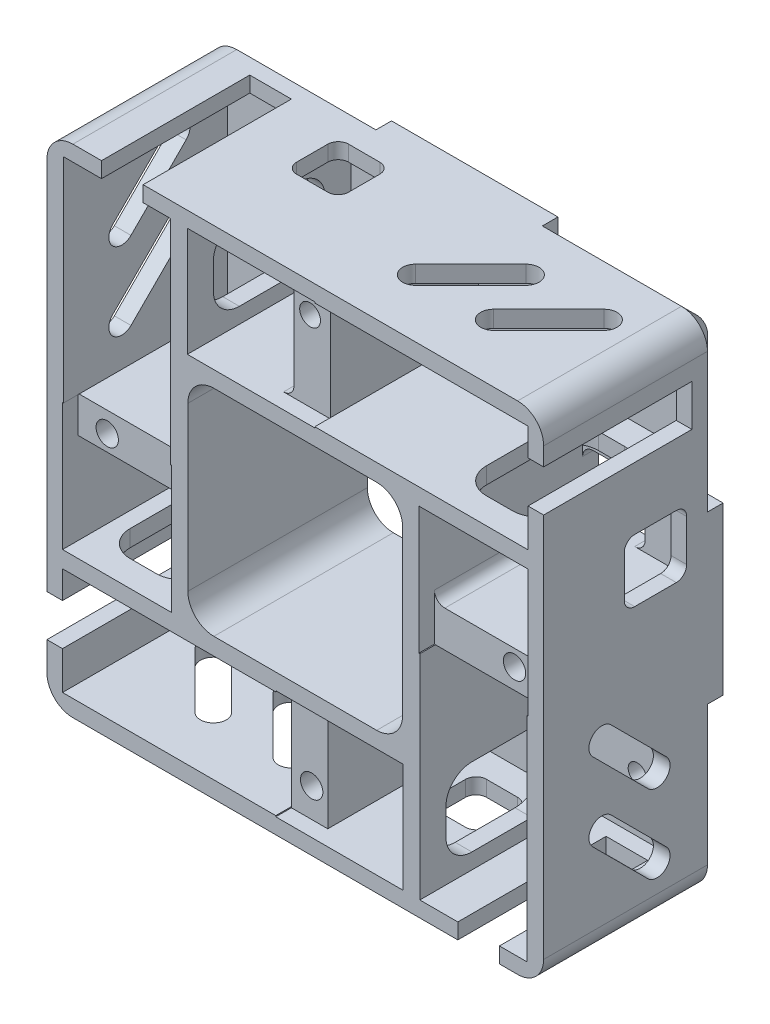
SolidWorks part; units mm, degrees
ref_plane "正面" through (0, 0, 0) normal (0, 0, 1) x (1, 0, 0)
ref_plane "平面" through (0, 0, 0) normal (0, 1, 0) x (1, 0, 0)
ref_plane "右側面" through (0, 0, 0) normal (1, 0, 0) x (0, 0, -1)
sketch "ｽｹｯﾁ1" plane through (0, 0, 0) normal (0, 0, 1) x (1, 0, 0)
  line L7 (47.75, -47.75) -> (-47.75, -47.75)
  line L8 (47.75, -47.75) -> (47.75, 47.75)
  line L9 (47.75, 47.75) -> (-47.75, 47.75)
  line L10 (-47.75, -47.75) -> (-47.75, 47.75)
  line L11 (47.75, -47.75) -> (-47.75, 47.75) construction
  line L12 (47.75, 47.75) -> (-47.75, -47.75) construction
  circle A0 centre (34.25, 34.25) radius 1.75
  circle A1 centre (-34.25, 34.25) radius 1.75
  circle A2 centre (-34.25, -34.25) radius 1.75
  circle A3 centre (34.25, -34.25) radius 1.75
  point P0 (0, 0)
  point P10 (0, 0)
  dimension "D1" = 95.5
  dimension "D2" = 13.5
  dimension "D3" = 13.5
  dimension "D4" = 13.5
  dimension "D5" = 13.5
  dimension "D6" = 13.5
  dimension "D7" = 13.5
  dimension "D8" = 13.5
  dimension "D9" = 13.5
  dimension "D10" = 3.5
extrude "ﾎﾞｽ - 押し出し1" add sketch "ｽｹｯﾁ1" along normal blind 3
sketch "ｽｹｯﾁ3" plane through (0, 0, 3) normal (0, 0, 1) x (1, 0, 0)
  line L29 (2.25, -23.75) -> (20.75, -23.75)
  line L30 (-47.75, 47.75) -> (47.75, 47.75)
  line L32 (-20.75, -2) -> (-20.75, -20.75)
  line L33 (-47.75, 47.75) -> (-47.75, -47.75)
  line L34 (-47.75, -47.75) -> (47.75, -47.75)
  line L35 (47.75, 47.75) -> (47.75, -47.75)
  line L36 (-44.75, 44.75) -> (-23.75, 44.75)
  line L37 (-44.75, 44.75) -> (-44.75, 3.75)
  line L38 (-44.75, 3.75) -> (-23.75, 3.75)
  line L39 (-23.75, 44.75) -> (-23.75, 3.75)
  line L40 (44.75, 44.75) -> (3.75, 44.75)
  line L42 (44.75, 23.75) -> (3.75, 23.75)
  line L43 (3.75, 44.75) -> (3.75, 23.75)
  line L44 (44.75, -44.75) -> (23.75, -44.75)
  line L45 (44.75, -44.75) -> (44.75, -3.75)
  line L46 (44.75, -3.75) -> (23.75, -3.75)
  line L47 (23.75, -44.75) -> (23.75, -3.75)
  line L48 (44.75, 44.75) -> (44.75, 23.75)
  line L49 (-44.75, -44.75) -> (-3.75, -44.75)
  line L50 (-44.75, -44.75) -> (-44.75, -23.75)
  line L51 (-44.75, -23.75) -> (-3.75, -23.75)
  line L52 (-3.75, -44.75) -> (-3.75, -23.75)
  line L54 (-20.75, 44.75) -> (-2.25, 44.75)
  line L55 (-20.75, 44.75) -> (-20.75, 23.75)
  line L57 (-2.25, 44.75) -> (-2.25, 23.75)
  line L58 (-44.75, -2.25) -> (-23.75, -2.25)
  line L59 (-44.75, -2.25) -> (-44.75, -20.75)
  line L60 (-44.75, -20.75) -> (20.75, -20.75)
  line L61 (20.75, 2) -> (20.75, -20.75)
  line L62 (-2, 20.75) -> (20.75, 20.75)
  line L64 (23.75, 2.25) -> (44.75, 2.25)
  line L65 (44.75, 20.75) -> (44.75, 2.25)
  line L66 (2.25, -44.75) -> (20.75, -44.75)
  line L67 (2.25, -44.75) -> (2.25, -20.75)
  line L69 (20.75, -44.75) -> (20.75, -23.75)
  line L70 (-20.75, -20.75) -> (-23.75, -20.75)
  line L71 (-23.75, -2.25) -> (-23.75, -20.75)
  line L72 (-2, 20.75) -> (-20.75, 20.75)
  line L74 (-2.25, 23.75) -> (-20.75, 23.75)
  line L75 (-20.75, 20.75) -> (-20.75, 23.75)
  line L77 (20.75, 2) -> (20.75, 20.75)
  line L78 (20.75, 20.75) -> (23.75, 20.75)
  line L79 (23.75, 2.25) -> (23.75, 20.75)
  line L80 (20.75, -20.75) -> (20.75, 2)
  line L81 (23.75, 20.75) -> (44.75, 20.75)
  line L82 (-20.75, 20.75) -> (-20.75, -2)
  dimension "D2" = 3
  dimension "D11" = 6
  dimension "D1" = 21
  dimension "D3" = 3
  dimension "D4" = 3
  dimension "D5" = 3
  dimension "D6" = 41
  dimension "D7" = 3
  dimension "D8" = 3
  dimension "D9" = 3
  dimension "D10" = 3
extrude "ﾎﾞｽ - 押し出し2" add sketch "ｽｹｯﾁ3" along normal blind 31.5
fillet "ﾌｨﾚｯﾄ1" radius 5 4 edges at (-47.75, -47.75, 17.25) (47.75, -47.75, 17.25) (47.75, 47.75, 17.25) (-47.75, 47.75, 17.25)
chamfer "面取り1" distance 3 angle 45 8 edges at (47.75, 0, 0) (46.2855, 46.2855, 0) (46.2855, -46.2855, 0) (0, 47.75, 0) (0, -47.75, 0) (-46.2855, 46.2855, 0) (-46.2855, -46.2855, 0) (-47.75, 0, 0)
sketch "ｽｹｯﾁ17" plane through (0, 0, 0) normal (0, 0, -1) x (-1, 0, 0)
  line L0 (-42.75, 47.75) -> (42.75, 47.75) construction
  line L1 (-16, 47.75) -> (16, 47.75)
  line L2 (-16, 47.75) -> (-16, 44.75)
  line L3 (-16, 44.75) -> (16, 44.75)
  line L4 (16, 47.75) -> (16, 44.75)
  line L5 (47.75, 42.75) -> (47.75, -42.75) construction
  line L6 (47.75, 16) -> (44.75, 16)
  line L7 (47.75, 16) -> (47.75, -16)
  line L8 (47.75, -16) -> (44.75, -16)
  line L9 (44.75, 16) -> (44.75, -16)
  line L10 (42.75, -47.75) -> (-42.75, -47.75) construction
  line L11 (16, -47.75) -> (-16, -47.75)
  line L12 (16, -47.75) -> (16, -44.75)
  line L13 (16, -44.75) -> (-16, -44.75)
  line L14 (-16, -47.75) -> (-16, -44.75)
  line L15 (-47.75, -42.75) -> (-47.75, 42.75) construction
  line L16 (-47.75, 16) -> (-44.75, 16)
  line L17 (-47.75, 16) -> (-47.75, -16)
  line L18 (-47.75, -16) -> (-44.75, -16)
  line L19 (-44.75, 16) -> (-44.75, -16)
  line L20 (42.75, 44.75) -> (-42.75, 44.75) construction
  line L21 (44.75, -42.75) -> (44.75, 42.75) construction
  line L22 (-42.75, -44.75) -> (42.75, -44.75) construction
  line L23 (-44.75, 42.75) -> (-44.75, -42.75) construction
  point P24 (-44.75, 0)
  point P26 (44.75, 0)
  point P27 (0, -44.75)
  point P28 (0, 44.75)
  dimension "D1" = 32
extrude "ﾎﾞｽ - 押し出し6" add sketch "ｽｹｯﾁ17" against normal blind 3
sketch "ｽｹｯﾁ19" plane through (0, 0, 0) normal (0, 0, -1) x (-1, 0, 0)
  line L0 (-47.75, 16) -> (-47.75, -16) construction
  line L1 (16, 47.75) -> (-16, 47.75) construction
  line L2 (47.75, -16) -> (47.75, 16) construction
  line L3 (-16, -47.75) -> (16, -47.75) construction
  circle A0 centre (0, 37.75) radius 2
  circle A1 centre (-37.75, 0) radius 2
  circle A2 centre (37.75, 0) radius 2
  circle A3 centre (0, -37.75) radius 2
  dimension "D1" = 4
  dimension "D2" = 10
  dimension "D3" = 10
  dimension "D4" = 10
  dimension "D5" = 10
extrude "ｶｯﾄ - 押し出し4" cut sketch "ｽｹｯﾁ19" against normal blind 2.8
sketch "ｽｹｯﾁ21" plane through (0, 0, 34.5) normal (0, 0, 1) x (1, 0, 0)
  line L0 (-44.75, -23.75) -> (-3.75, -23.75) construction
  line L1 (44.75, -3.75) -> (23.75, -3.75)
  line L2 (44.75, -3.75) -> (44.75, 2.25)
  line L3 (44.75, 2.25) -> (23.75, 2.25)
  line L4 (23.75, -3.75) -> (23.75, 2.25)
  line L5 (-3.75, -44.75) -> (2.25, -44.75)
  line L6 (-3.75, -44.75) -> (-3.75, -23.75)
  line L7 (-3.75, -23.75) -> (2.25, -23.75)
  line L8 (2.25, -44.75) -> (2.25, -23.75)
  line L9 (-44.75, 3.75) -> (-23.75, 3.75)
  line L10 (-44.75, 3.75) -> (-44.75, -2.25)
  line L11 (-44.75, -2.25) -> (-23.75, -2.25)
  line L12 (-23.75, 3.75) -> (-23.75, -2.25)
  line L13 (3.75, 44.75) -> (-2.25, 44.75)
  line L14 (3.75, 44.75) -> (3.75, 23.75)
  line L15 (3.75, 23.75) -> (-2.25, 23.75)
  line L16 (-2.25, 44.75) -> (-2.25, 23.75)
  line L17 (-23.75, 44.75) -> (-23.75, 3.75) construction
  line L18 (44.75, 23.75) -> (3.75, 23.75) construction
  line L19 (23.75, -44.75) -> (23.75, -3.75) construction
  line L20 (-2.25, 44.75) -> (-2.25, 23.75) construction
extrude "ｶｯﾄ - 押し出し6" cut sketch "ｽｹｯﾁ21" against normal blind 3
sketch "ｽｹｯﾁ34" plane through (2.25, 0, 0) normal (1, 0, 0) x (0, 0, -1)
  line L0 (-31.5, -23.75) -> (-3, -23.75) construction
  line L1 (-3, -44.75) -> (-31.5, -44.75)
  line L2 (-3, -44.75) -> (-3, -23.75)
  line L3 (-3, -23.75) -> (-31.5, -23.75)
  line L4 (-31.5, -44.75) -> (-31.5, -23.75)
extrude "ﾎﾞｽ - 押し出し8" add sketch "ｽｹｯﾁ34" along normal blind 1
sketch "ｽｹｯﾁ35" plane through (0, -2.25, 0) normal (0, -1, 0) x (-1, 0, 0)
  line L1 (44.75, -31.5) -> (23.75, -31.5)
  line L2 (44.75, -31.5) -> (44.75, -3)
  line L3 (44.75, -3) -> (23.75, -3)
  line L4 (23.75, -31.5) -> (23.75, -3)
extrude "ﾎﾞｽ - 押し出し9" add sketch "ｽｹｯﾁ35" along normal blind 1
sketch "ｽｹｯﾁ36" plane through (-2.25, 0, 0) normal (-1, 0, 0) x (0, 0, 1)
  line L1 (3, 44.75) -> (31.5, 44.75)
  line L2 (3, 44.75) -> (3, 23.75)
  line L3 (3, 23.75) -> (31.5, 23.75)
  line L4 (31.5, 44.75) -> (31.5, 23.75)
extrude "ﾎﾞｽ - 押し出し10" add sketch "ｽｹｯﾁ36" along normal blind 1
sketch "ｽｹｯﾁ37" plane through (0, 2.25, 0) normal (0, 1, 0) x (1, 0, 0)
  line L1 (23.75, -31.5) -> (44.75, -31.5)
  line L2 (23.75, -31.5) -> (23.75, -3)
  line L3 (23.75, -3) -> (44.75, -3)
  line L4 (44.75, -31.5) -> (44.75, -3)
extrude "ﾎﾞｽ - 押し出し11" add sketch "ｽｹｯﾁ37" along normal blind 1
sketch "ｽｹｯﾁ20" plane through (0, 0, 31.5) normal (0, 0, 1) x (1, 0, 0)
  line L1 (23.75, 3.25) -> (44.75, 3.25) construction
  line L2 (-3.25, 23.75) -> (-3.25, 44.75) construction
  line L3 (-23.75, -3.25) -> (-44.75, -3.25) construction
  line L4 (3.75, 44.75) -> (-3.25, 44.75) construction
  line L5 (3.25, -23.75) -> (3.25, -44.75) construction
  line L14 (-44.75, 3.75) -> (-44.75, -3.25) construction
  line L18 (-3.75, -44.75) -> (3.25, -44.75) construction
  line L20 (44.75, -3.75) -> (44.75, 3.25) construction
  circle A0 centre (-39.15, -0.15) radius 2.15
  circle A3 centre (-0.15, 39.15) radius 2
  circle A5 centre (39.15, 0.15) radius 2.15
  circle A7 centre (0.15, -39.15) radius 2.15
  dimension "D2" = 4.3
  dimension "D3" = 5.6
  dimension "D4" = 3.1
  dimension "D5" = 3.1
  dimension "D6" = 5.6
  dimension "D7" = 3.1
  dimension "D8" = 5.6
  dimension "D9" = 4
  dimension "D10" = 3.1
  dimension "D11" = 5.6
extrude "ｶｯﾄ - 押し出し5" cut sketch "ｽｹｯﾁ20" against normal blind 5
sketch "ｽｹｯﾁ22" plane through (0, 0, 0) normal (0, 0, -1) x (-1, 0, 0)
  circle A0 centre (-37.75, 0) radius 1.75
  circle A1 centre (0, 37.75) radius 1.75
  circle A2 centre (37.75, 0) radius 1.75
  circle A3 centre (0, -37.75) radius 1.75
  dimension "D1" = 3.5
extrude "ｶｯﾄ - 押し出し7" [suppressed] cut sketch "ｽｹｯﾁ22" against normal blind 3
sketch "ｽｹｯﾁ23" plane through (0, 0, 3) normal (0, 0, 1) x (1, 0, 0)
  line L0 (-44.75, 44.75) -> (-23.75, 44.75) construction
  line L1 (-37.25, 44.75) -> (-29.25, 44.75)
  line L2 (-37.25, 44.75) -> (-37.25, 47.75)
  line L3 (-37.25, 47.75) -> (-29.25, 47.75)
  line L4 (-29.25, 44.75) -> (-29.25, 47.75)
  line L5 (42.75, 47.75) -> (-42.75, 47.75) construction
  line L6 (44.75, 44.75) -> (44.75, 23.75) construction
  line L7 (44.75, 39.25) -> (47.75, 39.25)
  line L8 (44.75, 39.25) -> (44.75, 31.25)
  line L9 (44.75, 31.25) -> (47.75, 31.25)
  line L10 (47.75, 39.25) -> (47.75, 31.25)
  line L11 (47.75, -42.75) -> (47.75, 42.75) construction
  line L12 (44.75, -44.75) -> (23.75, -44.75) construction
  line L13 (39.25, -44.75) -> (31.25, -44.75)
  line L14 (39.25, -44.75) -> (39.25, -47.75)
  line L15 (39.25, -47.75) -> (31.25, -47.75)
  line L16 (31.25, -44.75) -> (31.25, -47.75)
  line L17 (-42.75, -47.75) -> (42.75, -47.75) construction
  line L18 (-44.75, -44.75) -> (-44.75, -23.75) construction
  line L19 (-44.75, -37.25) -> (-47.75, -37.25)
  line L20 (-44.75, -37.25) -> (-44.75, -29.25)
  line L21 (-44.75, -29.25) -> (-47.75, -29.25)
  line L22 (-47.75, -37.25) -> (-47.75, -29.25)
  line L23 (-47.75, 42.75) -> (-47.75, -42.75) construction
  circle A0 centre (34.25, 34.25) radius 1.75 construction
  circle A1 centre (34.25, -34.25) radius 1.75 construction
  circle A2 centre (-34.25, 34.25) radius 1.75 construction
  circle A3 centre (-34.25, -34.25) radius 1.75 construction
  dimension "D4" = 5
  dimension "D1" = 8
  dimension "D2" = 8
  dimension "D3" = 5
  dimension "D5" = 5
  dimension "D6" = 5
extrude "ｶｯﾄ - 押し出し8" cut sketch "ｽｹｯﾁ23" along normal through all from offset 3
sketch "ｽｹｯﾁ24" plane through (0, 47.75, 0) normal (0, 1, 0) x (1, 0, 0)
  line L0 (-29.25, -34.5) -> (-29.25, -6) construction
  line L1 (-16, -3) -> (-42.75, -3) construction
  line L3 (-18.25, -8) -> (-8.25, -8)
  line L4 (-18.25, -8) -> (-18.25, -18)
  line L5 (-18.25, -18) -> (-8.25, -18)
  line L6 (-8.25, -8) -> (-8.25, -18)
  line L7 (-18.25, -8) -> (-8.25, -18) construction
  line L8 (-18.25, -18) -> (-8.25, -8) construction
  circle A0 centre (-13.25, -13) radius 5 construction
  dimension "D2" = 10
  dimension "D3" = 10
  dimension "D1" = 16
  dimension "D4" = 10
extrude "ｶｯﾄ - 押し出し9" cut sketch "ｽｹｯﾁ24" against normal blind 10
sketch "ｽｹｯﾁ25" plane through (47.75, 0, 0) normal (1, 0, 0) x (0, 0, -1)
  line L0 (-34.5, 31.25) -> (-6, 31.25) construction
  line L1 (-3, 16) -> (-3, 42.75) construction
  line L3 (-7, 7.25) -> (-19, 7.25)
  line L4 (-7, 7.25) -> (-7, 19.25)
  line L5 (-7, 19.25) -> (-19, 19.25)
  line L6 (-19, 7.25) -> (-19, 19.25)
  line L7 (-7, 7.25) -> (-19, 19.25) construction
  line L8 (-7, 19.25) -> (-19, 7.25) construction
  circle A0 centre (-13, 13.25) radius 5 construction
  dimension "D1" = 18
  dimension "D2" = 10
  dimension "D3" = 10
  dimension "D4" = 12
extrude "ｶｯﾄ - 押し出し10" cut sketch "ｽｹｯﾁ25" against normal blind 10
sketch "ｽｹｯﾁ26" plane through (0, -47.75, 0) normal (0, -1, 0) x (-1, 0, 0)
  line L0 (-31.25, -34.5) -> (-31.25, -6) construction
  line L1 (-16, -3) -> (-42.75, -3) construction
  line L3 (-8.25, -18) -> (-18.25, -18)
  line L4 (-8.25, -18) -> (-8.25, -8)
  line L5 (-8.25, -8) -> (-18.25, -8)
  line L6 (-18.25, -18) -> (-18.25, -8)
  line L7 (-8.25, -18) -> (-18.25, -8) construction
  line L8 (-8.25, -8) -> (-18.25, -18) construction
  circle A0 centre (-13.25, -13) radius 5 construction
  dimension "D1" = 18
  dimension "D2" = 10
  dimension "D3" = 10
  dimension "D4" = 10
extrude "ｶｯﾄ - 押し出し11" cut sketch "ｽｹｯﾁ26" against normal blind 10
sketch "ｽｹｯﾁ27" plane through (-47.75, 0, 0) normal (-1, 0, 0) x (0, 0, 1)
  line L0 (34.5, -29.25) -> (6, -29.25) construction
  line L1 (3, -16) -> (3, -42.75) construction
  line L3 (8, -16.25) -> (18, -16.25)
  line L4 (8, -16.25) -> (8, -6.25)
  line L5 (8, -6.25) -> (18, -6.25)
  line L6 (18, -16.25) -> (18, -6.25)
  line L7 (8, -16.25) -> (18, -6.25) construction
  line L8 (8, -6.25) -> (18, -16.25) construction
  circle A0 centre (13, -11.25) radius 5 construction
  dimension "D1" = 18
  dimension "D2" = 10
  dimension "D3" = 10
  dimension "D4" = 10
extrude "ｶｯﾄ - 押し出し12" cut sketch "ｽｹｯﾁ27" against normal blind 10
sketch "ｽｹｯﾁ28" plane through (0, 0, 3) normal (0, 0, 1) x (1, 0, 0)
  line L0 (-23.75, -3.25) -> (-23.75, -20.75) construction
  line L1 (35.75, 15.25) -> (23.75, 15.25)
  line L2 (35.75, 15.25) -> (35.75, 3.25)
  line L3 (35.75, 3.25) -> (23.75, 3.25)
  line L4 (23.75, 15.25) -> (23.75, 3.25)
  line L5 (-15.25, 35.75) -> (-3.25, 35.75)
  line L6 (-15.25, 35.75) -> (-15.25, 23.75)
  line L7 (-15.25, 23.75) -> (-3.25, 23.75)
  line L8 (-3.25, 35.75) -> (-3.25, 23.75)
  line L9 (-35.75, -15.25) -> (-23.75, -15.25)
  line L10 (-35.75, -15.25) -> (-35.75, -3.25)
  line L11 (-35.75, -3.25) -> (-23.75, -3.25)
  line L12 (-23.75, -15.25) -> (-23.75, -3.25)
  line L13 (15.25, -35.75) -> (3.25, -35.75)
  line L14 (15.25, -35.75) -> (15.25, -23.75)
  line L15 (15.25, -23.75) -> (3.25, -23.75)
  line L16 (3.25, -35.75) -> (3.25, -23.75)
  line L20 (3.25, -44.75) -> (3.25, -23.75) construction
  line L21 (3.25, -23.75) -> (20.75, -23.75) construction
  line L22 (-44.75, -3.25) -> (-23.75, -3.25) construction
  line L23 (-3.25, 23.75) -> (-20.75, 23.75) construction
  line L24 (-3.25, 44.75) -> (-3.25, 23.75) construction
  line L25 (44.75, 3.25) -> (23.75, 3.25) construction
  line L26 (23.75, 3.25) -> (23.75, 20.75) construction
  dimension "D1" = 12
  dimension "D2" = 12
  dimension "D3" = 12
  dimension "D4" = 12
extrude "ｶｯﾄ - 押し出し13" cut sketch "ｽｹｯﾁ28" against normal through all and the other way through all
fillet "ﾌｨﾚｯﾄ2" radius 2 16 edges at (-35.75, -3.25, 1.5) (-35.75, -15.25, 1.5) (-23.75, -15.25, 1.5) (-15.25, 35.75, 1.5) (-15.25, 23.75, 1.5) (-3.25, 35.75, 1.5) (35.75, 3.25, 1.5) (35.75, 15.25, 1.5) (23.75, 15.25, 1.5) (3.25, -35.75, 1.5) (15.25, -23.75, 1.5) (15.25, -35.75, 1.5) (-23.75, -3.25, 15.75) (-3.25, 23.75, 15.75) (23.75, 3.25, 15.75) (3.25, -23.75, 15.75)
fillet "ﾌｨﾚｯﾄ3" radius 2 16 edges at (8.25, -46.25, 8) (18.25, -46.25, 8) (18.25, -46.25, 18) (8.25, -46.25, 18) (46.25, 19.25, 19) (46.25, 19.25, 7) (46.25, 7.25, 7) (46.25, 7.25, 19) (-18.25, 46.25, 18) (-18.25, 46.25, 8) (-8.25, 46.25, 8) (-8.25, 46.25, 18) (-46.25, -16.25, 18) (-46.25, -16.25, 8) (-46.25, -6.25, 8) (-46.25, -6.25, 18)
ref_plane "平面1" through (0, 0, 29.5) normal (0, 0, -1) x (-1, 0, 0)
sketch "ｽｹｯﾁ38" plane through (0, 0, 34.5) normal (0, 0, 1) x (1, 0, 0)
  line L0 (44.75, -44.75) -> (39.25, -44.75) construction
  line L1 (44.75, -3.75) -> (44.55, -3.75)
  line L2 (44.75, -3.75) -> (44.75, -44.75)
  line L3 (44.75, -44.75) -> (44.55, -44.75)
  line L4 (44.55, -3.75) -> (44.55, -44.75)
  line L5 (-44.75, -44.75) -> (-44.75, -23.75) construction
  line L6 (23.75, -3.75) -> (23.95, -3.75)
  line L7 (23.75, -3.75) -> (23.75, -44.75)
  line L8 (23.75, -44.75) -> (23.95, -44.75)
  line L9 (23.95, -3.75) -> (23.95, -44.75)
  line L10 (-3.75, -44.75) -> (-44.75, -44.75)
  line L11 (-3.75, -44.75) -> (-3.75, -44.55)
  line L12 (-3.75, -44.55) -> (-44.75, -44.55)
  line L13 (-44.75, -44.75) -> (-44.75, -44.55)
  line L14 (-44.75, 44.75) -> (-37.25, 44.75) construction
  line L15 (-3.75, -23.75) -> (-44.75, -23.75)
  line L16 (-3.75, -23.75) -> (-3.75, -23.95)
  line L17 (-3.75, -23.95) -> (-44.75, -23.95)
  line L18 (-44.75, -23.75) -> (-44.75, -23.95)
  line L19 (-44.75, 3.75) -> (-44.55, 3.75)
  line L20 (-44.75, 3.75) -> (-44.75, 44.75)
  line L21 (-44.75, 44.75) -> (-44.55, 44.75)
  line L22 (-44.55, 3.75) -> (-44.55, 44.75)
  line L23 (-44.75, 44.75) -> (-23.75, 44.75) construction
  line L24 (-23.75, 3.75) -> (-23.95, 3.75)
  line L25 (-23.75, 3.75) -> (-23.75, 44.75)
  line L26 (-23.75, 44.75) -> (-23.95, 44.75)
  line L27 (-23.95, 3.75) -> (-23.95, 44.75)
  line L28 (44.75, 23.75) -> (3.75, 23.75) construction
  line L29 (3.75, 23.75) -> (44.75, 23.75)
  line L30 (3.75, 23.75) -> (3.75, 23.95)
  line L31 (3.75, 23.95) -> (44.75, 23.95)
  line L32 (44.75, 23.75) -> (44.75, 23.95)
  line L33 (3.75, 44.75) -> (3.75, 23.75) construction
  line L34 (44.75, 44.75) -> (44.75, 23.75) construction
  line L36 (3.75, 44.75) -> (44.75, 44.75)
  line L37 (3.75, 44.75) -> (3.75, 44.55)
  line L38 (3.75, 44.55) -> (44.75, 44.55)
  line L39 (44.75, 44.75) -> (44.75, 44.55)
  line L40 (44.75, 44.75) -> (44.75, 39.25) construction
  line L41 (31.25, -44.75) -> (23.75, -44.75) construction
  dimension "D1" = 0.2
extrude "ﾎﾞｽ - 押し出し12" add sketch "ｽｹｯﾁ38" against normal up to surface (31.5 mm away) up to face at (-24.25, -34.25, 3)
sketch "ｽｹｯﾁ40" plane through (0, 0, 3) normal (0, 0, 1) x (1, 0, 0)
  line L1 (20.75, 20.75) -> (-20.75, 20.75)
  line L2 (20.75, 20.75) -> (20.75, -20.75)
  line L3 (20.75, -20.75) -> (-20.75, -20.75)
  line L4 (-20.75, 20.75) -> (-20.75, -20.75)
  line L5 (20.75, 20.75) -> (-20.75, -20.75) construction
  line L6 (20.75, -20.75) -> (-20.75, 20.75) construction
  point P0 (0, 0)
extrude "ﾎﾞｽ - 押し出し13" add sketch "ｽｹｯﾁ40" along normal through all
sketch "ｽｹｯﾁ39" plane through (0, 0, 0) normal (0, 0, -1) x (-1, 0, 0)
  line L1 (20.65, -20.65) -> (-20.65, -20.65)
  line L2 (20.65, -20.65) -> (20.65, 20.65)
  line L3 (20.65, 20.65) -> (-20.65, 20.65)
  line L4 (-20.65, -20.65) -> (-20.65, 20.65)
  line L5 (20.65, -20.65) -> (-20.65, 20.65) construction
  line L6 (20.65, 20.65) -> (-20.65, -20.65) construction
  point P0 (0, 0)
  dimension "D1" = 41.3
extrude "ｶｯﾄ - 押し出し14" cut sketch "ｽｹｯﾁ39" against normal through all
fillet "ﾌｨﾚｯﾄ4" radius 5 4 edges at (-20.65, 20.65, 17.25) (-20.65, -20.65, 17.25) (20.65, -20.65, 17.25) (20.65, 20.65, 17.25)
sketch "ｽｹｯﾁ41" plane through (-47.75, 0, 0) normal (-1, 0, 0) x (0, 0, 1)
  line L0 (18, -8.25) -> (18, 42.75) construction
  line L1 (34.5, 42.75) -> (3, 42.75) construction
  line L2 (12.6967, 22.5533) -> (23.3033, 11.9467) construction
  line L3 (14.4645, 24.3211) -> (25.0711, 13.7145)
  line L4 (10.9289, 20.7855) -> (21.5355, 10.1789)
  line L5 (23.3033, 26.9467) -> (12.6967, 37.5533) construction
  line L6 (21.5355, 25.1789) -> (10.9289, 35.7855)
  line L7 (25.0711, 28.7145) -> (14.4645, 39.3211)
  arc A0 (14.4645, 24.3211) -> (10.9289, 20.7855) centre (12.6967, 22.5533) ccw
  arc A1 (21.5355, 10.1789) -> (25.0711, 13.7145) centre (23.3033, 11.9467) ccw
  arc A2 (21.5355, 25.1789) -> (25.0711, 28.7145) centre (23.3033, 26.9467) ccw
  arc A3 (14.4645, 39.3211) -> (10.9289, 35.7855) centre (12.6967, 37.5533) ccw
  point P7 (18, 17.25)
  point P13 (18, 32.25)
  point P20 (18, 2.25)
  dimension "D1" = 45
  dimension "D2" = 5
  dimension "D3" = 15
  dimension "D4" = 15
  dimension "D5" = 15
extrude "ｶｯﾄ - 押し出し15" cut sketch "ｽｹｯﾁ41" against normal blind 10
sketch "ｽｹｯﾁ44" plane through (0, 0, 0) normal (0, 1, 0) x (1, 0, 0)
  line L0 (0, 0) -> (0, -34.5) construction
  line L1 (42.75, -34.5) -> (-29.25, -34.5) construction
pattern_circular "円形ﾊﾟﾀｰﾝ1" count 4 over 360 about axis through (0, 0, 0) along (0, 0, 1) of "ｶｯﾄ - 押し出し15"
sketch "ｽｹｯﾁ45" plane through (-20.75, 0, 0) normal (1, 0, 0) x (0, 0, -1)
  line L0 (-34.5, 23.75) -> (-3, 23.75) construction
  line L1 (-8, 26.75) -> (-29.5, 26.75)
  line L2 (-8, 26.75) -> (-8, 41.75)
  line L3 (-8, 41.75) -> (-29.5, 41.75)
  line L4 (-29.5, 26.75) -> (-29.5, 41.75)
  line L5 (-8, 26.75) -> (-29.5, 41.75) construction
  line L6 (-8, 41.75) -> (-29.5, 26.75) construction
  line L7 (-34.5, 44.75) -> (-34.5, 23.75) construction
  line L8 (-3, 44.75) -> (-3, 23.75) construction
  point P0 (-18.75, 34.25)
  dimension "D1" = 15
  dimension "D2" = 10.5
  dimension "D3" = 5
  dimension "D4" = 5
extrude "ｶｯﾄ - 押し出し16" cut sketch "ｽｹｯﾁ45" against normal blind 10
fillet "ﾌｨﾚｯﾄ5" radius 5 4 edges at (-22.35, 26.75, 8) (-22.35, 26.75, 29.5) (-22.35, 41.75, 29.5) (-22.35, 41.75, 8)
pattern_circular "円形ﾊﾟﾀｰﾝ2" count 4 over 360 about axis through (0, 0, 0) along (0, 0, 1) of "ﾌｨﾚｯﾄ5", "ｶｯﾄ - 押し出し16"
